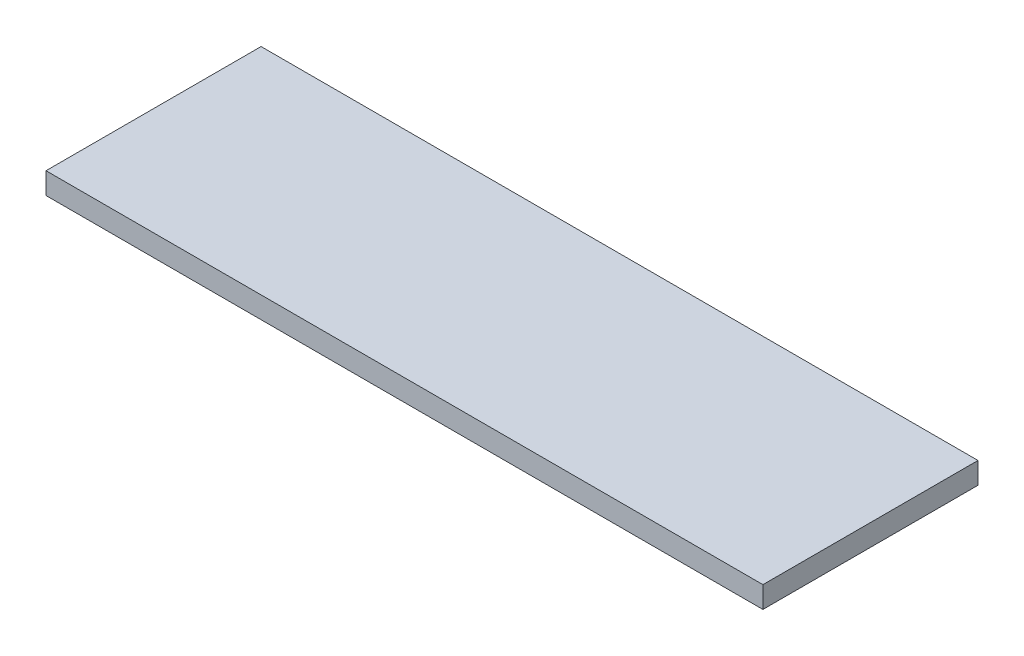
SolidWorks part; units mm, degrees
ref_plane "Front Plane" through (0, 0, 0) normal (0, 0, 1) x (1, 0, 0)
ref_plane "Top Plane" through (0, 0, 0) normal (0, 1, 0) x (1, 0, 0)
ref_plane "Right Plane" through (0, 0, 0) normal (1, 0, 0) x (0, 0, -1)
sketch "Sketch1" plane through (0, 0, 0) normal (0, 1, 0) x (1, 0, 0)
  line L1 (284, -46.75) -> (-216, -46.75)
  line L2 (284, -46.75) -> (284, 103.25)
  line L3 (284, 103.25) -> (-216, 103.25)
  line L4 (-216, -46.75) -> (-216, 103.25)
  line L5 (284, -46.75) -> (-216, 103.25) construction
  line L6 (284, 103.25) -> (-216, -46.75) construction
  point P0 (34, 28.25)
  dimension "D1" = 150
  dimension "D2" = 500
extrude "Boss-Extrude1" add sketch "Sketch1" along normal blind 15
